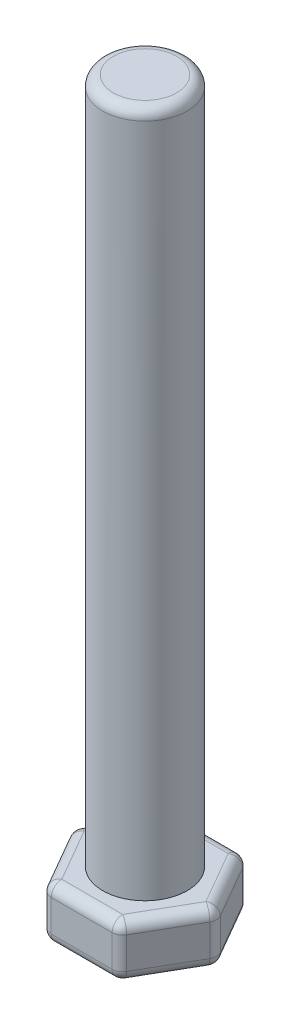
SolidWorks part; units mm, degrees
ref_plane "Front Plane" through (0, 0, 0) normal (0, 0, 1) x (1, 0, 0)
ref_plane "Top Plane" through (0, 0, 0) normal (0, 1, 0) x (1, 0, 0)
ref_plane "Right Plane" through (0, 0, 0) normal (1, 0, 0) x (0, 0, -1)
sketch "Sketch1" plane through (0, 0, 0) normal (0, 1, 0) x (1, 0, 0)
  circle A0 centre (0, 0) radius 4
  dimension "D1" = 8
extrude "Boss-Extrude1" add sketch "Sketch1" along normal blind 65
cosmetic thread "Cosmetic Thread1" parameters "D1"=10, "D2"=6.619
sketch "Sketch2" plane through (0, 0, 0) normal (0, -1, 0) x (1, 0, 0)
  line L1 (-3.4641, -6) -> (3.4641, -6)
  line L2 (3.4641, -6) -> (6.9282, 0)
  line L3 (6.9282, 0) -> (3.4641, 6)
  line L4 (3.4641, 6) -> (-3.4641, 6)
  line L5 (-3.4641, 6) -> (-6.9282, 0)
  line L6 (-6.9282, 0) -> (-3.4641, -6)
  circle A0 centre (0, 0) radius 6 construction
  dimension "D1" = 12
extrude "Boss-Extrude2" add sketch "Sketch2" along normal blind 5
fillet "Fillet1" radius 1 1 edges at (0, 65, 4)
fillet "Fillet2" radius 1 18 edges at (-5.1962, 0, -3) (5.1962, 0, 3) (-5.1962, -5, -3) (5.1962, -5, 3) (5.1962, 0, -3) (0, -5, 6) (0, 0, 6) (5.1962, -5, -3) (-5.1962, 0, 3) (-5.1962, -5, 3) (0, 0, -6) (0, -5, -6) (-3.4641, -2.5, -6) (6.9282, -2.5, 0) (3.4641, -2.5, 6) (-3.4641, -2.5, 6) (-6.9282, -2.5, 0) (3.4641, -2.5, -6)
